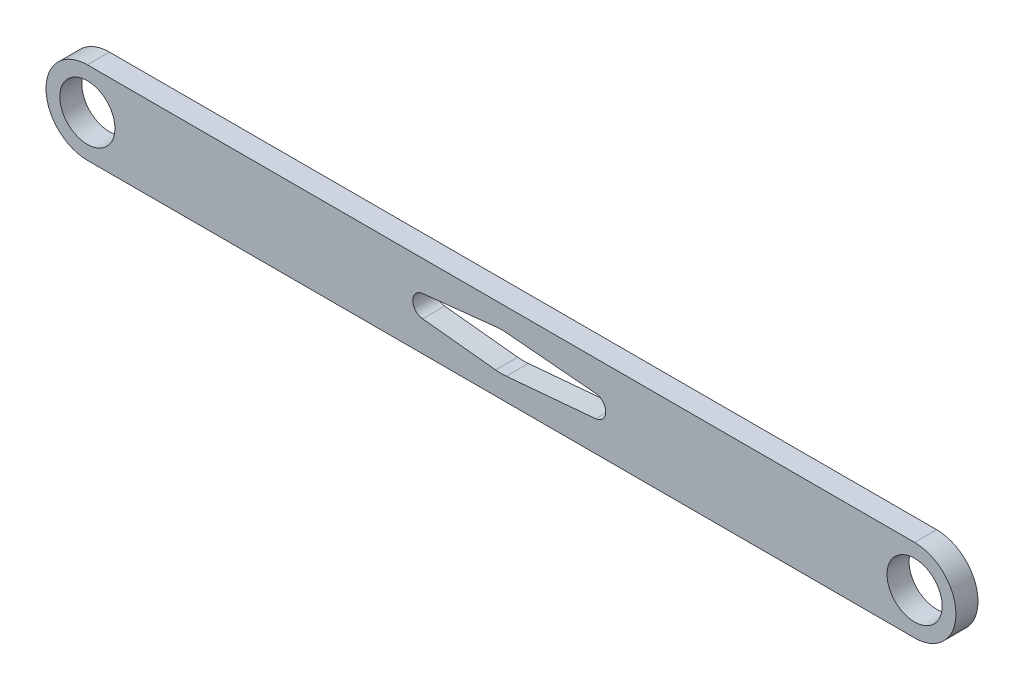
SolidWorks part; units mm, degrees
ref_plane "Front Plane" through (0, 0, 0) normal (0, 0, 1) x (1, 0, 0)
ref_plane "Top Plane" through (0, 0, 0) normal (0, 1, 0) x (1, 0, 0)
ref_plane "Right Plane" through (0, 0, 0) normal (1, 0, 0) x (0, 0, -1)
sketch "Sketch1" plane through (0, 0, 0) normal (0, 0, 1) x (1, 0, 0)
  line L0 (75, 0) -> (-75, 0) construction
  line L1 (75, -7.5) -> (-75, -7.5)
  line L2 (75, 7.5) -> (-75, 7.5)
  line L3 (0, 7.5) -> (0, -7.5) construction
  line L4 (-0.9651, 3.3974) -> (-14.2115, 1.9888)
  line L9 (0.9668, 3.4151) -> (17.1749, 1.9923)
  line L10 (0.9668, -3.4151) -> (17.1749, -1.9923)
  line L11 (-0.9651, -3.3974) -> (-14.2115, -1.9888)
  arc A0 (75, -7.5) -> (75, 7.5) centre (75, 0) ccw
  arc A1 (-75, 7.5) -> (-75, -7.5) centre (-75, 0) ccw
  circle A2 centre (75, 0) radius 5
  circle A3 centre (-75, 0) radius 5
  arc A6 (0.9668, 3.4151) -> (-0.9651, 3.3974) centre (0.0923, -6.5466) ccw
  arc A7 (-0.9651, -3.3974) -> (0.9668, -3.4151) centre (0.0923, 6.5466) ccw
  arc A8 (-14.2115, 1.9888) -> (-14.2115, -1.9888) centre (-14, 0) ccw
  arc A9 (17.1749, 1.9923) -> (17.1749, -1.9923) centre (17, 0) cw
  point P2 (0, 0)
  point P14 (19, 0)
  point P15 (-14, 0)
  point P16 (0, 3.5)
  point P17 (0, -3.5)
  point P30 (0, 3.5)
  point P33 (0, -3.5)
  dimension "D2" = 10
  dimension "D8" = 2
  dimension "D9" = 2
  dimension "D10" = 10
  dimension "D1" = 150
  dimension "D3" = 15
  dimension "D4" = 19
  dimension "D5" = 14
  dimension "D6" = 3.5
  dimension "D7" = 3.5
extrude "Boss-Extrude1" add sketch "Sketch1" along normal blind 4
